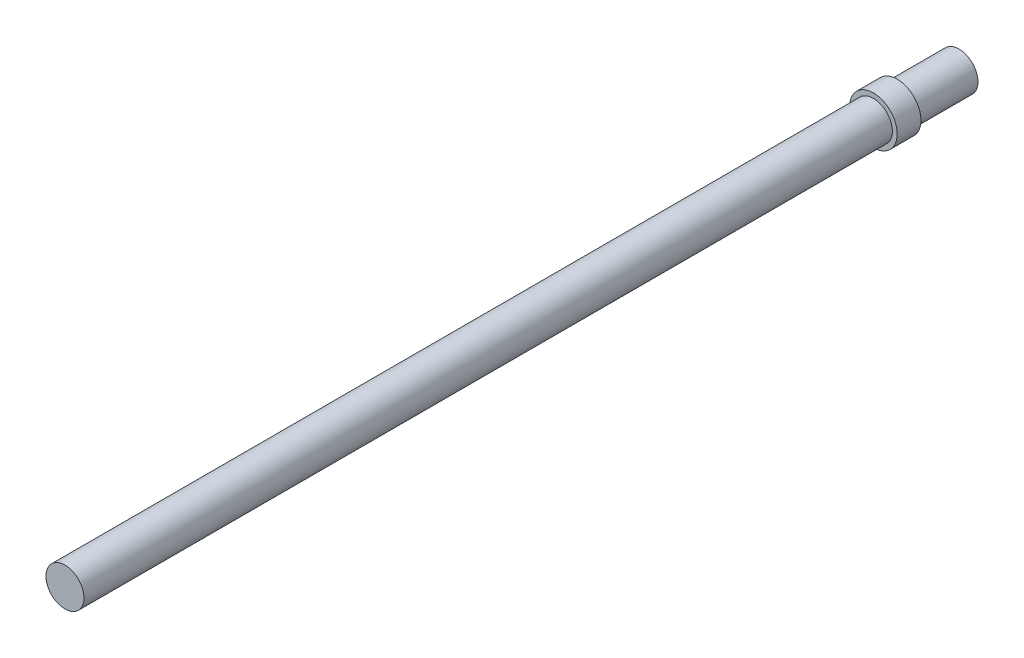
SolidWorks part; units mm, degrees
ref_plane "Front Plane" through (0, 0, 0) normal (0, 0, 1) x (1, 0, 0)
ref_plane "Top Plane" through (0, 0, 0) normal (0, 1, 0) x (1, 0, 0)
ref_plane "Right Plane" through (0, 0, 0) normal (1, 0, 0) x (0, 0, -1)
sketch "Sketch1" plane through (0, 0, 0) normal (0, 0, 1) x (1, 0, 0)
  circle A0 centre (0, 0) radius 4
extrude "Boss-Extrude1" add sketch "Sketch1" along normal blind 170
sketch "Sketch2" plane through (0, 0, 0) normal (0, 0, 1) x (1, 0, 0)
  circle A0 centre (0, 0) radius 5
extrude "Boss-Extrude2" add sketch "Sketch2" against normal blind 5
sketch "Sketch3" plane through (0, 0, 0) normal (0, 0, 1) x (1, 0, 0)
  circle A0 centre (0, 0) radius 4
extrude "Boss-Extrude3" add sketch "Sketch3" against normal blind 18
